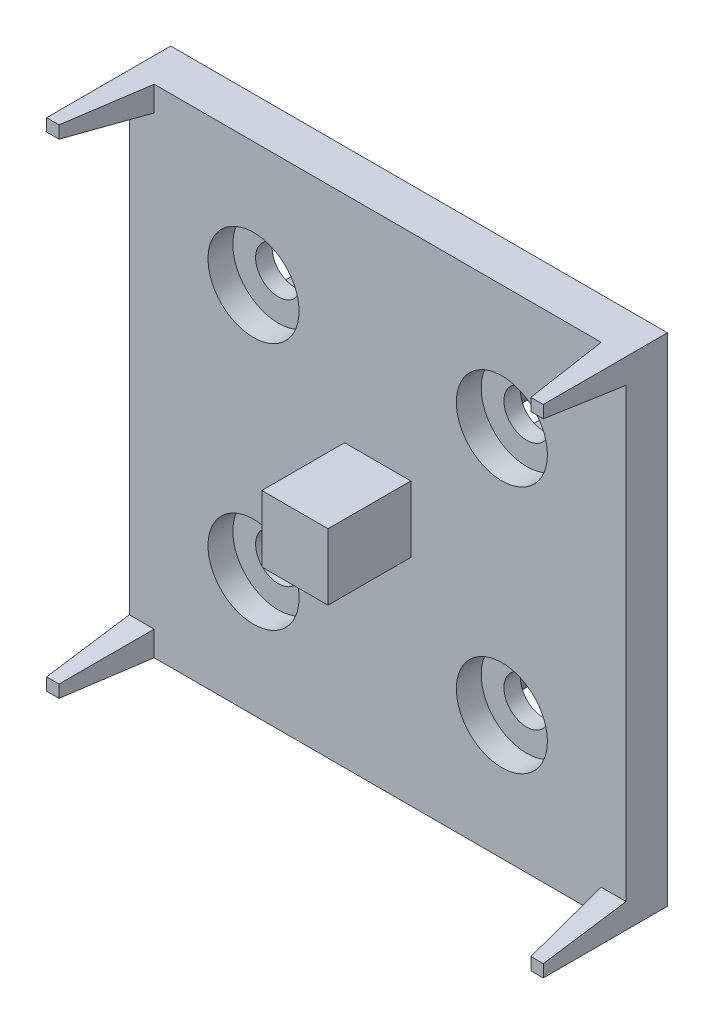
SolidWorks part; units mm, degrees
ref_plane "정면" through (0, 0, 0) normal (0, 0, 1) x (1, 0, 0)
ref_plane "윗면" through (0, 0, 0) normal (0, 1, 0) x (1, 0, 0)
ref_plane "우측면" through (0, 0, 0) normal (1, 0, 0) x (0, 0, -1)
sketch "스케치1" plane through (0, 0, 0) normal (0, 0, 1) x (1, 0, 0)
  line L1 (-30, 30) -> (30, 30)
  line L2 (-30, 30) -> (-30, -30)
  line L3 (-30, -30) -> (30, -30)
  line L4 (30, 30) -> (30, -30)
  line L5 (-30, 30) -> (30, -30) construction
  line L6 (-30, -30) -> (30, 30) construction
  point P0 (0, 0)
  dimension "D1" = 60
  dimension "D2" = 60
extrude "보스-돌출1" add sketch "스케치1" along normal blind 5
sketch "스케치3" plane through (0, 0, 5) normal (0, 0, 1) x (1, 0, 0)
  line L1 (-30, -30) -> (-27, -30)
  line L2 (-30, -30) -> (-30, -27)
  line L3 (-30, -27) -> (-27, -27)
  line L4 (-27, -30) -> (-27, -27)
  dimension "D1" = 3
  dimension "D2" = 3
extrude "보스-돌출3" add sketch "스케치3" along normal blind 10
sketch "스케치4" plane through (-27, 0, 0) normal (1, 0, 0) x (0, 0, -1)
  line L0 (-15, -27) -> (-15, -28.5)
  line L1 (-15, -30) -> (-15, -27) construction
  line L2 (-15, -28.5) -> (-5, -27)
  line L3 (-5, -27) -> (-15, -27)
extrude "컷-돌출1" cut sketch "스케치4" against normal through all
sketch "스케치5" plane through (0, -30, 0) normal (0, -1, 0) x (1, 0, 0)
  line L5 (-28.5, 15) -> (-27, 15)
  line L6 (-30, 15) -> (-27, 15) construction
  line L7 (-27, 15) -> (-27, 5)
  line L8 (-27, 5) -> (-28.5, 15)
extrude "컷-돌출2" cut sketch "스케치5" against normal blind 10
sketch "스케치6" plane through (0, 0, 0) normal (1, 0, 0) x (0, 0, -1)
  line L0 (-23.9815, 0) -> (27.3926, 0) construction
pattern_circular "원형 패턴1" count 4 over 360 about axis through (0, 0, 0) along (0, 0, 1) of "보스-돌출3", "컷-돌출1", "컷-돌출2"
hole_wizard "M5 소켓 머리 캡 나사용 카운터보어2" positions "스케치7" profile "스케치8" counterbore size "M5" standard "KS" end condition through all
sketch "스케치7" plane through (0, 0, 5) normal (0, 0, 1) x (1, 0, 0)
  line L0 (27, 30) -> (-27, 30) construction
  line L1 (-30, 27) -> (-30, -27) construction
  line L2 (30, -27) -> (30, 27) construction
  line L3 (-27, -30) -> (27, -30) construction
  point P0 (-15, 15)
  point P2 (15, 15)
  point P4 (15, -15)
  point P6 (-15, -15)
  point P17 (18.4717, 16.362)
  point P18 (0, 0)
  dimension "D1" = 15
  dimension "D2" = 15
  dimension "D3" = 15
  dimension "D4" = 15
  dimension "D5" = 15
  dimension "D6" = 15
  dimension "D7" = 15
  dimension "D8" = 15
sketch "스케치8" plane through (-15, 15, 5) normal (1, 0, 0) x (0, -1, 0)
  line L0 (0, 0) -> (0, 5)
  line L1 (0, 5) -> (2.75, 5)
  line L3 (2.75, 5) -> (2.75, 3)
  line L4 (2.75, 3) -> (5.5, 3)
  line L5 (5.5, 3) -> (5.5, 0)
  line L7 (5.5, 0) -> (0, 0)
  line L11 (0, -6.35) -> (0, 107.95) construction
  dimension "관통 구멍 지름" = 5.5
  dimension "관통 구멍 깊이" = 5
  dimension "카운터보어 지름" = 11
  dimension "카운터보어 깊이" = 3
sketch "스케치9" plane through (0, 0, 0) normal (0, 0, -1) x (-1, 0, 0)
  line L7 (-20.05, 2.5) -> (-20.05, 8.545)
  line L8 (-18.05, 2.5) -> (-20.05, 2.5)
  line L9 (-18.05, -2.5) -> (-18.05, 2.5)
  line L10 (-9.95, 2.5) -> (-9.95, 8.545)
  line L11 (-11.95, 2.5) -> (-9.95, 2.5)
  line L12 (-11.95, -2.5) -> (-11.95, 2.5)
  line L13 (-11.95, -2.5) -> (-9.95, -2.5)
  line L14 (-15, 10.5) -> (-0.7637, 10.5) construction
  line L15 (-9.95, -2.5) -> (-9.95, -8.545)
  line L16 (-18.05, -2.5) -> (-20.05, -2.5)
  line L17 (-20.05, -2.5) -> (-20.05, -8.545)
  line L18 (2.5, 20.05) -> (8.545, 20.05)
  line L19 (2.5, 18.05) -> (2.5, 20.05)
  line L20 (-2.5, 18.05) -> (2.5, 18.05)
  line L21 (2.5, 9.95) -> (8.545, 9.95)
  line L22 (2.5, 11.95) -> (2.5, 9.95)
  line L23 (-2.5, 11.95) -> (2.5, 11.95)
  line L24 (-2.5, 11.95) -> (-2.5, 9.95)
  line L25 (-2.5, 9.95) -> (-8.545, 9.95)
  line L26 (-2.5, 18.05) -> (-2.5, 20.05)
  line L27 (-2.5, 20.05) -> (-8.545, 20.05)
  line L28 (10.5, 15) -> (10.5, 0.7637) construction
  line L29 (20.05, -2.5) -> (20.05, -8.545)
  line L30 (18.05, -2.5) -> (20.05, -2.5)
  line L31 (18.05, 2.5) -> (18.05, -2.5)
  line L32 (9.95, -2.5) -> (9.95, -8.545)
  line L33 (11.95, -2.5) -> (9.95, -2.5)
  line L34 (11.95, 2.5) -> (11.95, -2.5)
  line L35 (11.95, 2.5) -> (9.95, 2.5)
  line L36 (9.95, 2.5) -> (9.95, 8.545)
  line L37 (18.05, 2.5) -> (20.05, 2.5)
  line L38 (20.05, 2.5) -> (20.05, 8.545)
  line L39 (15, -10.5) -> (0.7637, -10.5) construction
  line L40 (-2.5, -20.05) -> (-8.545, -20.05)
  line L41 (-2.5, -18.05) -> (-2.5, -20.05)
  line L42 (2.5, -18.05) -> (-2.5, -18.05)
  line L43 (-2.5, -9.95) -> (-8.545, -9.95)
  line L44 (-2.5, -11.95) -> (-2.5, -9.95)
  line L45 (2.5, -11.95) -> (-2.5, -11.95)
  line L46 (2.5, -11.95) -> (2.5, -9.95)
  line L47 (2.5, -9.95) -> (8.545, -9.95)
  line L48 (2.5, -18.05) -> (2.5, -20.05)
  line L49 (2.5, -20.05) -> (8.545, -20.05)
  line L50 (-10.5, -15) -> (-10.5, -0.7637) construction
  arc A1 (-20.05, 8.545) -> (-9.95, 8.545) centre (-15, 3) cw
  circle A2 centre (-15, 15) radius 2.75 construction
  arc A3 (-20.05, -8.545) -> (-9.95, -8.545) centre (-15, -3) ccw
  circle A4 centre (-15, -15) radius 2.75 construction
  arc A5 (8.545, 20.05) -> (8.545, 9.95) centre (3, 15) cw
  arc A6 (-8.545, 20.05) -> (-8.545, 9.95) centre (-3, 15) ccw
  arc A7 (20.05, -8.545) -> (9.95, -8.545) centre (15, -3) cw
  arc A8 (20.05, 8.545) -> (9.95, 8.545) centre (15, 3) ccw
  arc A9 (-8.545, -20.05) -> (-8.545, -9.95) centre (-3, -15) cw
  arc A10 (8.545, -20.05) -> (8.545, -9.95) centre (3, -15) ccw
  point P72 (0, 0)
  dimension "D1" = 7.5
  dimension "D14" = 7.5
  dimension "D2" = 6.045
  dimension "D3" = 2
  dimension "D4" = 2
  dimension "D5" = 18
  dimension "D6" = 5.05
  dimension "D7" = 6.045
  dimension "D8" = 3.05
  dimension "D9" = 2
  dimension "D10" = 10.5
  dimension "D11" = 0
  dimension "D12" = 6.045
  dimension "D13" = 6.045
  dimension "D15" = 6.1
  dimension "D16" = 5
  dimension "D17" = 5
  dimension "D18" = 10.1
  dimension "D20" = 12
  dimension "D21" = 12
  dimension "D19" = 4
extrude "보스-돌출4" add sketch "스케치9" along normal blind 10
chamfer "모따기1" distance 1.5 angle 45 48 edges at (-20.05, 5.5225, -10) (-19.05, 2.5, -10) (-18.05, 0, -10) (-19.05, -2.5, -10) (-20.05, -5.5225, -10) (-15, -10.5, -10) (-9.95, -5.5225, -10) (-10.95, -2.5, -10) (-11.95, 0, -10) (-10.95, 2.5, -10) (-9.95, 5.5225, -10) (-15, 10.5, -10) (-5.5225, -20.05, -10) (-2.5, -19.05, -10) (0, -18.05, -10) (2.5, -19.05, -10) (5.5225, -20.05, -10) (10.5, -15, -10) (5.5225, -9.95, -10) (2.5, -10.95, -10) (0, -11.95, -10) (-2.5, -10.95, -10) (-5.5225, -9.95, -10) (-10.5, -15, -10) (5.5225, 20.05, -10) (2.5, 19.05, -10) (0, 18.05, -10) (-2.5, 19.05, -10) (-5.5225, 20.05, -10) (-10.5, 15, -10) (-5.5225, 9.95, -10) (-2.5, 10.95, -10) (0, 11.95, -10) (2.5, 10.95, -10) (5.5225, 9.95, -10) (10.5, 15, -10) (20.05, -5.5225, -10) (19.05, -2.5, -10) (18.05, 0, -10) (19.05, 2.5, -10) (20.05, 5.5225, -10) (15, 10.5, -10) (9.95, 5.5225, -10) (10.95, 2.5, -10) (11.95, 0, -10) (10.95, -2.5, -10) (9.95, -5.5225, -10) (15, -10.5, -10)
sketch "스케치10" plane through (0, 0, 5) normal (0, 0, 1) x (1, 0, 0)
  line L1 (-4, 4) -> (4, 4)
  line L2 (-4, 4) -> (-4, -4)
  line L3 (-4, -4) -> (4, -4)
  line L4 (4, 4) -> (4, -4)
  line L5 (-4, 4) -> (4, -4) construction
  line L6 (-4, -4) -> (4, 4) construction
  point P0 (0, 0)
  dimension "D1" = 8
  dimension "D2" = 8
extrude "보스-돌출5" add sketch "스케치10" along normal blind 10
